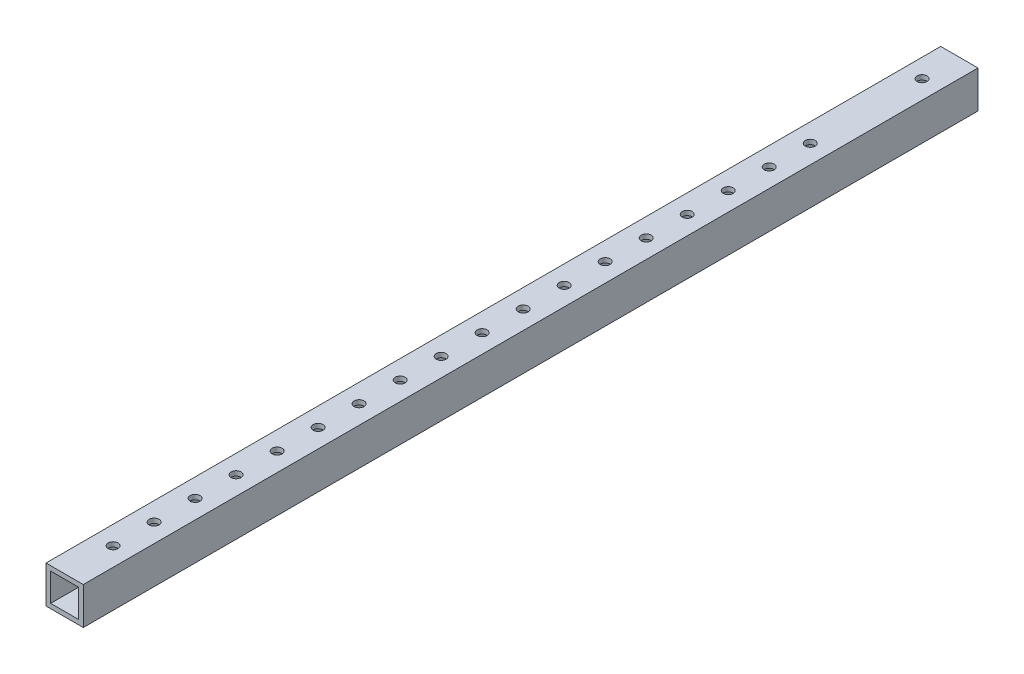
SolidWorks part; units mm, degrees
material "6061-T6 (SS)"
ref_plane "Front" through (0, 0, 0) normal (0, 0, 1) x (1, 0, 0)
ref_plane "Top" through (0, 0, 0) normal (0, 1, 0) x (1, 0, 0)
ref_plane "Right" through (0, 0, 0) normal (1, 0, 0) x (0, 0, -1)
sketch "Sketch1" plane through (0, 0, 0) normal (0, 0, 1) x (1, 0, 0)
  line L0 (-9.525, 9.525) -> (9.525, 9.525)
  line L1 (-12.7, -12.7) -> (12.7, -12.7)
  line L2 (-12.7, -12.7) -> (-12.7, 12.7)
  line L3 (-12.7, 12.7) -> (12.7, 12.7)
  line L4 (12.7, -12.7) -> (12.7, 12.7)
  line L5 (-12.7, -12.7) -> (12.7, 12.7) construction
  line L6 (-12.7, 12.7) -> (12.7, -12.7) construction
  line L7 (9.525, -9.525) -> (9.525, 9.525)
  line L8 (-9.525, -9.525) -> (9.525, -9.525)
  line L9 (-9.525, -9.525) -> (-9.525, 9.525)
  point P0 (0, 0)
  dimension "D1" = 25.4
  dimension "D2" = 3.175
extrude "Extrude1" add sketch "Sketch1" against normal blind 609.6
hole_wizard "1/4 Clearance Hole1" positions "Sketch3" profile "Sketch2" hole size "1/4" standard "Ansi Inch" end condition through all
sketch "Sketch3" plane through (0, 12.7, 0) normal (0, 1, 0) x (-1, 0, 0)
  line L0 (12.7, -584.2) -> (-12.7, -584.2) construction
  line L1 (12.7, -609.6) -> (12.7, 0) construction
  line L2 (-12.7, -609.6) -> (-12.7, 0) construction
  line L4 (-12.7, -609.6) -> (12.7, -609.6) construction
  point P0 (0, -584.2)
  dimension "D1" = 25.4
sketch "Sketch2" plane through (0, 12.7, -584.2) normal (1, 0, 0) x (0, 0, 1)
  line L0 (0, 0) -> (0, 25.4)
  line L1 (0, 25.4) -> (3.3782, 25.4)
  line L2 (3.3782, 25.4) -> (3.3782, 0)
  line L5 (3.3782, 0) -> (0, 0)
  line L11 (0, -6.35) -> (0, 107.95) construction
  dimension "Thru Hole Dia." = 6.7564
  dimension "Thru Hole Depth" = 25.4
hole_wizard "1/4 Clearance Hole2" positions "Sketch5" profile "Sketch4" hole size "1/4" standard "Ansi Inch" end condition through all
sketch "Sketch5" plane through (0, 12.7, 0) normal (0, 1, 0) x (-1, 0, 0)
  line L0 (-12.7, -508) -> (12.7, -508) construction
  line L1 (-12.7, -609.6) -> (-12.7, 0) construction
  line L2 (12.7, -609.6) -> (12.7, 0) construction
  circle A0 centre (0, -584.2) radius 3.3782 construction
  point P0 (0, -508)
  dimension "D1" = 76.2
sketch "Sketch4" plane through (0, 12.7, -508) normal (1, 0, 0) x (0, 0, 1)
  line L0 (0, 0) -> (0, 25.4)
  line L1 (0, 25.4) -> (3.3782, 25.4)
  line L2 (3.3782, 25.4) -> (3.3782, 0)
  line L5 (3.3782, 0) -> (0, 0)
  line L11 (0, -6.35) -> (0, 107.95) construction
  dimension "Thru Hole Dia." = 6.7564
  dimension "Thru Hole Depth" = 25.4
pattern_linear "LPattern1" count 18 spacing 27.94 along (0, 0, 1) of "1/4 Clearance Hole2"
